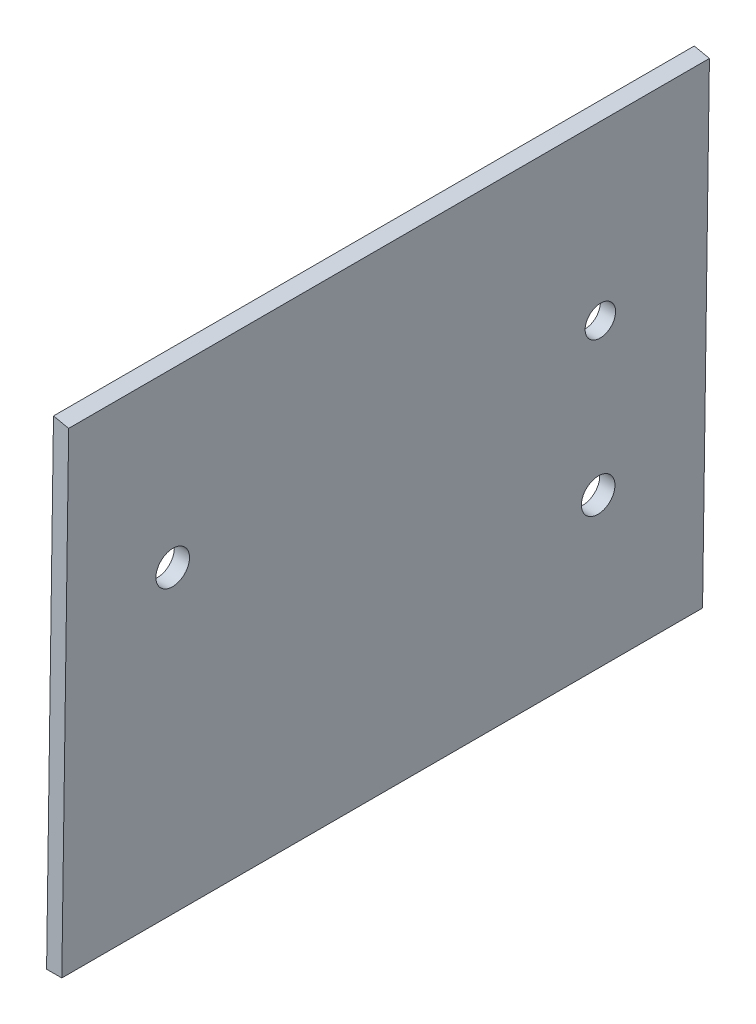
SolidWorks part; units mm, degrees
material "Pine"
ref_plane "Front Plane" through (0, 0, 0) normal (0, 0, 1) x (1, 0, 0)
ref_plane "Top Plane" through (0, 0, 0) normal (0, 1, 0) x (1, 0, 0)
ref_plane "Right Plane" through (0, 0, 0) normal (1, 0, 0) x (0, 0, -1)
sketch "Sketch1" plane through (0, 0, 0) normal (0, 0, 1) x (1, 0, 0)
  line L0 (0, 0) -> (5.7627, 402.6498)
  line L1 (5.7627, 402.6498) -> (18.4247, 400)
  line L2 (18.4247, 400) -> (12.7, 0)
  line L3 (12.7, 0) -> (0, 0)
  dimension "D1" = 400
  dimension "D2" = 12.7
  dimension "D3" = 79
extrude "Boss-Extrude1" add sketch "Sketch1" along normal blind 534.6
sketch "Sketch2" plane through (12.6974, -0.1817, 0) normal (0.9999, -0.0143, 0) x (0, 0, -1)
  line L0 (0, 0.1817) -> (0, 400.2227) construction
  line L1 (-534.6, 0.1817) -> (0, 0.1817) construction
  circle A0 centre (-88.9, 254.1817) radius 12.7
  dimension "D1" = 25.4
  dimension "D3" = 254
  dimension "D2" = 88.9
extrude "Cut-Extrude1" cut sketch "Sketch2" against normal blind 18.288
sketch "Sketch3" plane through (12.6974, -0.1817, 0) normal (0.9999, -0.0143, 0) x (0, 0, -1)
  line L0 (-534.6, 0.1817) -> (0, 0.1817) construction
  line L1 (0, 0.1817) -> (0, 400.2227) construction
  circle A0 centre (-88.9, 127.1817) radius 14
  dimension "D1" = 28
  dimension "D2" = 127
  dimension "D3" = 88.9
extrude "Cut-Extrude2" cut sketch "Sketch3" against normal blind 18.288
sketch "Sketch4" plane through (12.6974, -0.1817, 0) normal (0.9999, -0.0143, 0) x (0, 0, -1)
  line L0 (-534.6, 0.1817) -> (-534.6, 400.2227) construction
  line L1 (-534.6, 0.1817) -> (0, 0.1817) construction
  circle A0 centre (-445.7, 254.1817) radius 14
  dimension "D1" = 28
  dimension "D2" = 88.9
  dimension "D3" = 254
extrude "Cut-Extrude3" cut sketch "Sketch4" against normal blind 18.288
